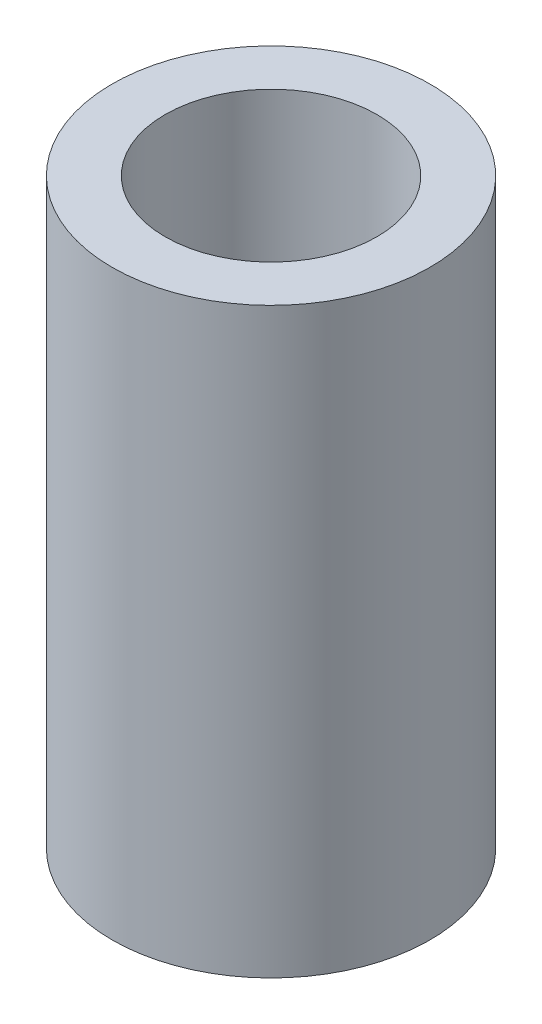
SolidWorks part; units mm, degrees
ref_plane "Front Plane" through (0, 0, 0) normal (0, 0, 1) x (1, 0, 0)
ref_plane "Top Plane" through (0, 0, 0) normal (0, 1, 0) x (1, 0, 0)
ref_plane "Right Plane" through (0, 0, 0) normal (1, 0, 0) x (0, 0, -1)
sketch "Sketch1" plane through (0, 0, 0) normal (0, 0, 1) x (1, 0, 0)
  line L0 (-2, 0) -> (-3, 0)
  line L1 (-3, 0) -> (-3, -11)
  line L2 (-3, -11) -> (-2, -11)
  line L3 (-2, -11) -> (-2, 0)
  line L4 (0, 0) -> (0, -11) construction
  dimension "D1" = 2
  dimension "D2" = 3
  dimension "D3" = 11
revolve "Revolve1" add sketch "Sketch1" angle 360 about L4
